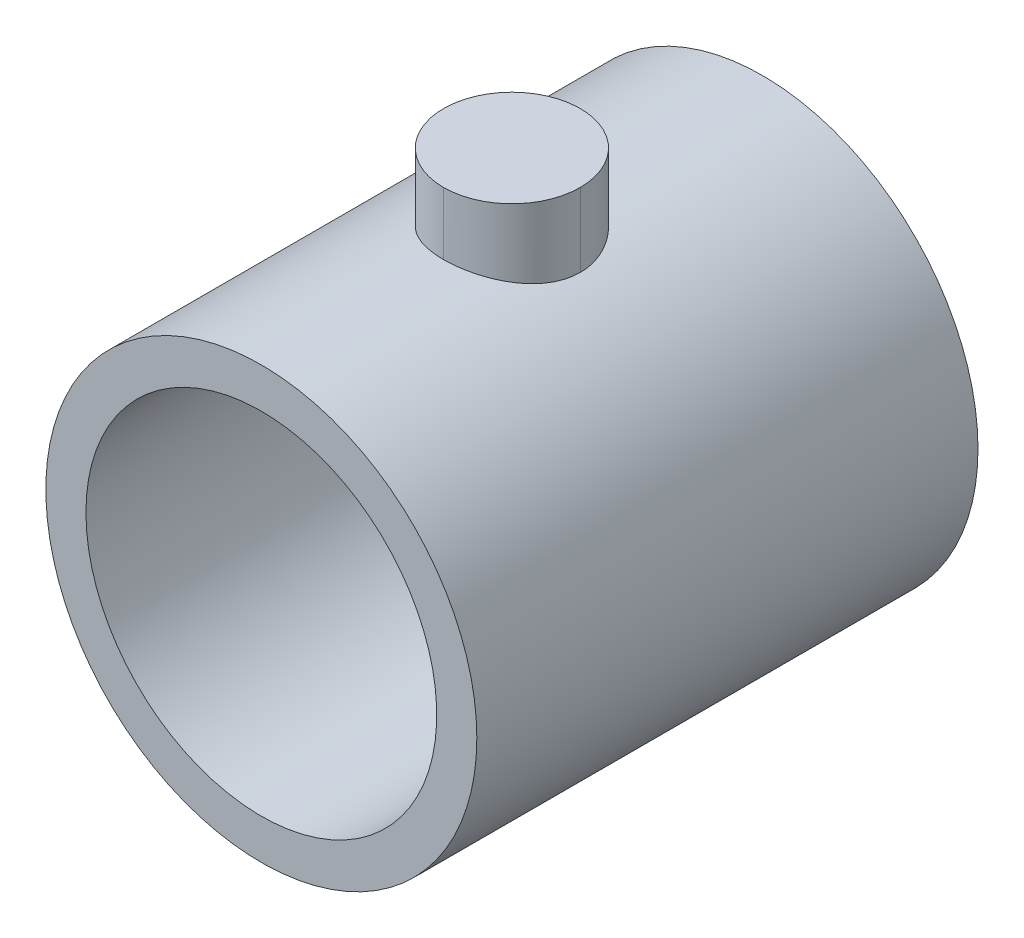
SolidWorks part; units mm, degrees
ref_plane "Front Plane" through (0, 0, 0) normal (0, 0, 1) x (1, 0, 0)
ref_plane "Top Plane" through (0, 0, 0) normal (0, 1, 0) x (1, 0, 0)
ref_plane "Right Plane" through (0, 0, 0) normal (1, 0, 0) x (0, 0, -1)
ref_plane "Plane1" through (0, 0, 624.8) normal (0, 0, -1) x (-1, 0, 0)
sketch "Sketch1" plane through (0, 0, 624.8) normal (0, 0, -1) x (-1, 0, 0)
  circle A0 centre (299.1, 352.3) radius 21.5
extrude "Boss-Extrude1" add sketch "Sketch1" against normal blind 50
sketch "Sketch2" plane through (0, 0, 674.8) normal (0, 0, 1) x (1, 0, 0)
  circle A0 centre (-299.1, 352.3) radius 17.5
extrude "Cut-Extrude1" cut sketch "Sketch2" against normal through all
ref_plane "Plane2" through (0, 380.0366, 0) normal (0, 1, 0) x (1, 0, 0)
sketch "Sketch3" plane through (0, 380.0366, 0) normal (0, 1, 0) x (1, 0, 0)
  arc A0 (-292.2802, -649.8) -> (-299.1, -656.6198) centre (-299.1, -649.8) cw
  arc A1 (-299.1, -656.6198) -> (-292.2802, -649.8) centre (-299.1, -649.8) cw
extrude "Boss-Extrude2" add sketch "Sketch3" against normal up to next
